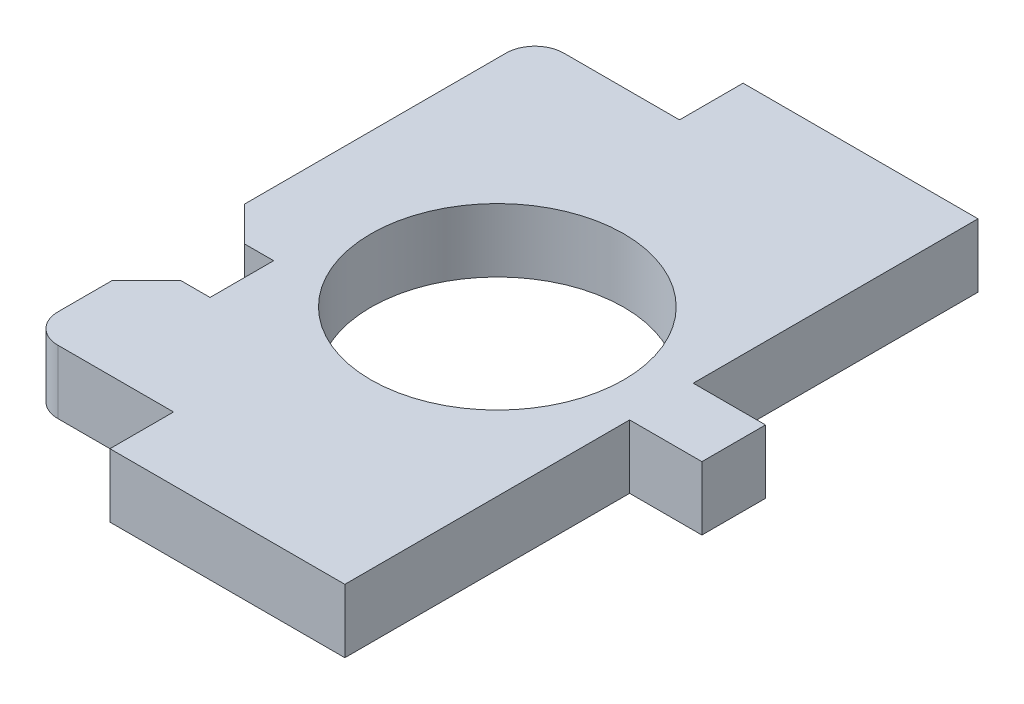
SolidWorks part; units mm, degrees
ref_plane "Front Plane" through (0, 0, 0) normal (0, 0, 1) x (1, 0, 0)
ref_plane "Top Plane" through (0, 0, 0) normal (0, 1, 0) x (1, 0, 0)
ref_plane "Right Plane" through (0, 0, 0) normal (1, 0, 0) x (0, 0, -1)
sketch "Sketch1" plane through (0, 0, 0) normal (0, 1, 0) x (1, 0, 0)
  line L0 (-13.8113, 22.225) -> (-19.5263, 22.225)
  line L1 (-13.8113, -22.225) -> (-6.8263, -22.225)
  line L2 (-13.8113, -22.225) -> (-13.8113, 22.225) construction
  line L3 (-13.8113, 22.225) -> (-6.8263, 22.225)
  line L4 (13.8112, -22.225) -> (13.8112, 22.225)
  line L5 (-13.8113, -22.225) -> (13.8112, 22.225) construction
  line L6 (-13.8113, 22.225) -> (13.8112, -22.225) construction
  line L7 (-19.5263, 22.225) -> (-19.5263, -3.2703)
  line L8 (-6.8263, 22.225) -> (-6.8263, 27.813)
  line L9 (-6.8263, 27.813) -> (13.8112, 27.813)
  line L10 (13.8112, 22.225) -> (13.8112, 27.813)
  line L11 (-19.5263, -3.2703) -> (-16.4782, -6.3182)
  line L12 (-6.8263, -22.225) -> (-6.8263, -27.813)
  line L13 (-6.8263, -27.813) -> (13.8113, -27.813)
  line L14 (13.8112, -22.225) -> (13.8113, -27.813)
  line L15 (-16.4782, -6.3182) -> (-13.9382, -6.3182)
  line L16 (-13.9382, -6.3182) -> (-13.9383, -11.9062)
  line L17 (-13.9383, -11.9062) -> (-16.4782, -11.9062)
  line L18 (-16.4782, -11.9062) -> (-19.5262, -14.9542)
  line L19 (-19.5262, -14.9542) -> (-19.5262, -22.225)
  line L20 (-19.5262, -22.225) -> (-13.8113, -22.225)
  point P0 (0, 0)
  dimension "D1" = 6.985
  dimension "D2" = 44.45
  dimension "D3" = 5.588
  dimension "D4" = 20.6375
  dimension "D5" = 45
  dimension "D6" = 45
  dimension "D7" = 5.588
  dimension "D8" = 12.7
  dimension "D9" = 5.588
  dimension "D10" = 10.3187
  dimension "D11" = 2.54
extrude "Boss-Extrude1" add sketch "Sketch1" along normal mid plane 5.588
sketch "Sketch2" plane through (0, 0, 0) normal (0, 1, 0) x (1, 0, 0)
  line L0 (13.8113, -27.813) -> (13.8112, 27.813) construction
  line L1 (13.8113, 2.794) -> (20.1613, 2.794)
  line L2 (13.8113, 2.794) -> (13.8113, -2.794)
  line L3 (13.8113, -2.794) -> (20.1613, -2.794)
  line L4 (20.1613, 2.794) -> (20.1613, -2.794)
  point P6 (13.8113, 0)
  dimension "D1" = 5.588
  dimension "D2" = 6.35
extrude "Boss-Extrude2" add sketch "Sketch2" along normal mid plane 5.588
sketch "Sketch3" plane through (0, 2.794, 0) normal (0, 1, 0) x (1, 0, 0)
  line L0 (7.2519, 9.7084) -> (7.2519, -9.7084)
  line L1 (7.2519, 0) -> (-2.9921, 0) construction
  arc A0 (2.809, -11.3909) -> (7.2519, -9.7084) centre (4.7119, -9.7084) ccw
  arc A1 (7.2519, 9.7084) -> (2.809, 11.3909) centre (4.7119, 9.7084) ccw
  spline S0 degree 3 poles (-2.9921, 0) (-2.8175, 4.7282) (-0.3908, 7.7719) (2.809, 11.3909) knots 0 0 0 0 0.692413 0.692413 0.692413 0.692413
  spline S1 degree 3 poles (-2.9921, 0) (-2.8175, -4.7282) (-0.3908, -7.7719) (2.809, -11.3909) knots 0 0 0 0 0.692413 0.692413 0.692413 0.692413
  dimension "D1" = 2.54
extrude "Cut-Extrude1" [suppressed] cut sketch "Sketch3" against normal through all
sketch "Sketch4" plane through (0, 2.794, 0) normal (0, 1, 0) x (1, 0, 0)
  line L0 (0, 0) -> (-0.6047, 0) construction
  circle A0 centre (-0.6047, 0) radius 11.1125
  dimension "D1" = 22.225
extrude "Cut-Extrude2" cut sketch "Sketch4" against normal through all
fillet "Fillet1" radius 2.54 2 edges at (-19.5263, 0, -22.225) (-19.5262, 0, 22.225)
